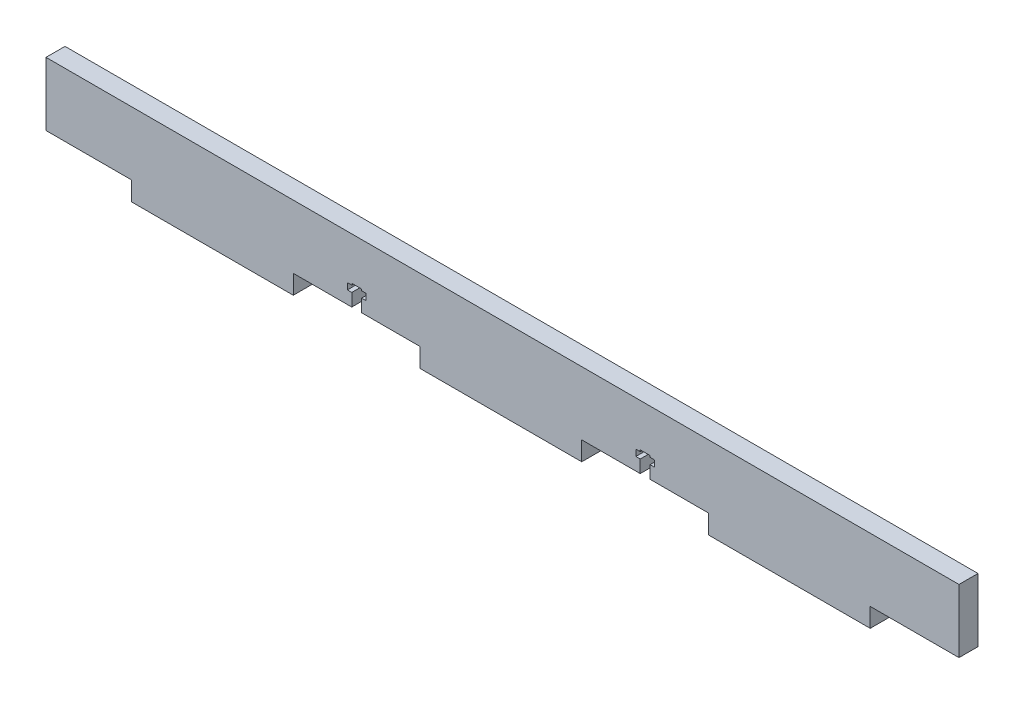
SolidWorks part; units mm, degrees
ref_plane "Płaszczyzna przednia" through (0, 0, 0) normal (0, 0, 1) x (1, 0, 0)
ref_plane "Płaszczyzna górna" through (0, 0, 0) normal (0, 1, 0) x (1, 0, 0)
ref_plane "Płaszczyzna prawa" through (0, 0, 0) normal (1, 0, 0) x (0, 0, -1)
sketch "Szkic1" plane through (0, 0, 0) normal (0, 0, 1) x (1, 0, 0)
  line L0 (-879.9, -6) -> (-591.9, -6)
  line L1 (-879.9, -6) -> (-879.9, 20)
  line L2 (-591.9, -6) -> (-591.9, 20)
  line L3 (-879.9, 20) -> (-591.9, 20)
  dimension "D1" = 26
  dimension "D2" = 288
extrude "Dodanie-wyciągnięcie1" add sketch "Szkic1" against normal blind 6
sketch "Szkic5" plane through (0, 0, 0) normal (0, 0, 1) x (1, 0, 0)
  line L0 (-879.9, 20) -> (-879.9, -6) construction
  line L1 (-892.9, 0) -> (-892.9, -6)
  line L5 (-852.9, 0) -> (-892.9, 0)
  line L6 (-852.9, 0) -> (-852.9, -6)
  line L7 (-852.9, -6) -> (-892.9, -6)
  dimension "D1" = 27
  dimension "D2" = 40
  dimension "D3" = 6
extrude "Wytnij-wyciągnięcie3" cut sketch "Szkic5" against normal blind 6
pattern_linear "Szyk liniowy1" count 4 spacing 91 along (1, 0, 0) of "Wytnij-wyciągnięcie3"
sketch "Szkic6" plane through (0, 0, 0) normal (0, 0, 1) x (1, 0, 0)
  line L0 (-852.9, 0) -> (-879.9, 0) construction
  line L1 (-780.35, 0) -> (-783.45, 0)
  line L2 (-780.35, 0) -> (-780.35, 4)
  line L3 (-780.35, 6.5) -> (-783.45, 6.5)
  line L4 (-783.45, 0) -> (-783.45, 4)
  line L5 (-780.35, 6) -> (-780.35, 6.5)
  line L6 (-778.975, 6) -> (-780.35, 6)
  line L7 (-778.975, 6) -> (-778.975, 4)
  line L8 (-778.975, 4) -> (-780.35, 4)
  line L9 (-784.825, 6) -> (-784.825, 4)
  line L10 (-783.45, 4) -> (-784.825, 4)
  line L11 (-783.45, 6) -> (-784.825, 6)
  line L12 (-783.45, 6) -> (-783.45, 6.5)
  line L14 (-801.9, 0) -> (-801.9, -6) construction
  point P14 (-781.9, 0)
  dimension "D1" = 6.5
  dimension "D2" = 0.5
  dimension "D3" = 5.85
  dimension "D4" = 1.375
  dimension "D5" = 3.1
  dimension "D6" = 2
  dimension "D7" = 20
extrude "Wytnij-wyciągnięcie4" cut sketch "Szkic6" against normal blind 6
pattern_linear "Szyk liniowy2" count 2 spacing 91 along (1, 0, 0) of "Wytnij-wyciągnięcie4"
equation "\"tolerancja_wpusy\"=0.2"
equation "\"dlugosc_wpustu_duzy\"=20"
equation "\"srednica_otworu_M3\"=3.1"
equation "\"szerokosc_nogi_T\"=3.1"
equation "\"dlugosc_T_30\"=11"
equation "\"grubosc_na_nakretke_kwadrat\"=2"
equation "\"szerokosc_na_nakretke_kwadrat\"=5.85"
equation "\"wyokosc_nadstawki_T\"=0.5"
equation "\"D2@Szkic6\" = \"wyokosc_nadstawki_T\""
equation "\"D3@Szkic6\"=\"szerokosc_na_nakretke_kwadrat\""
equation "\"D4@Szkic6\"=(\"szerokosc_na_nakretke_kwadrat\"-\"szerokosc_nogi_T\")/2"
equation "\"D6@Szkic6\"=\"grubosc_na_nakretke_kwadrat\""
